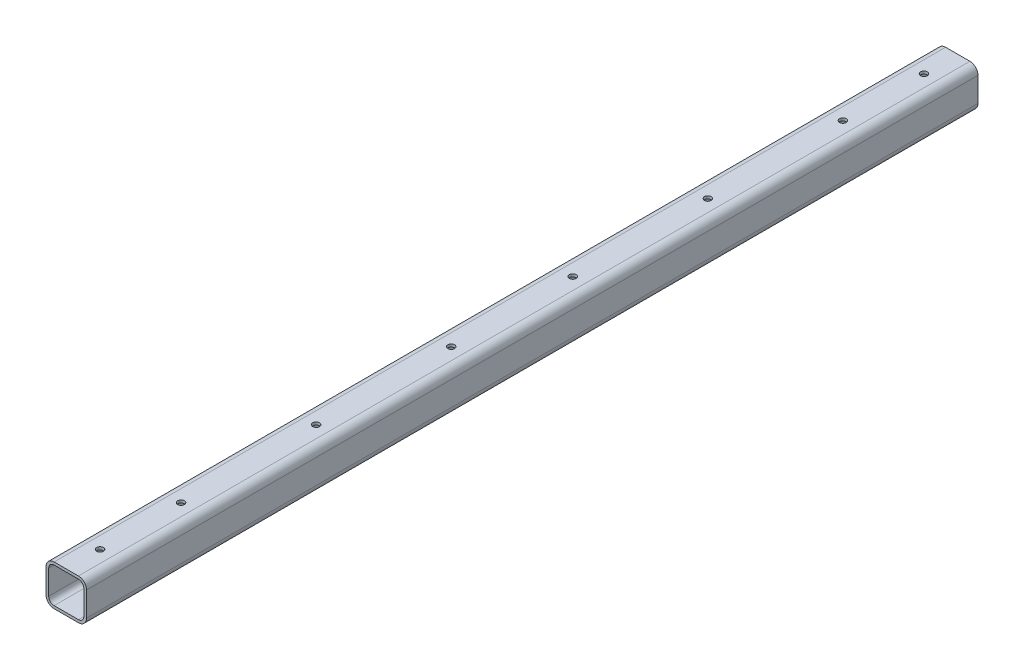
SolidWorks part; units mm, degrees
material "1.0038 (S235JRG2)"
ref_plane "Ebene vorne" through (0, 0, 0) normal (0, 0, 1) x (1, 0, 0)
ref_plane "Ebene oben" through (0, 0, 0) normal (0, 1, 0) x (1, 0, 0)
ref_plane "Ebene rechts" through (0, 0, 0) normal (1, 0, 0) x (0, 0, -1)
sketch "Skizze1" plane through (0, 0, 0) normal (0, 0, 1) x (1, 0, 0)
  line L0 (0, 0) -> (0, 67.8952) construction
  line L1 (-9, 15) -> (9, 15)
  line L2 (0, 0) -> (65.406, 0) construction
  line L3 (15, 9) -> (15, -9)
  line L4 (-15, 9) -> (-15, -9)
  line L5 (-9, -15) -> (9, -15)
  line L6 (-13, 9) -> (-13, -9)
  line L7 (-9, -13) -> (9, -13)
  line L8 (13, 9) -> (13, -9)
  line L9 (-9, 13) -> (9, 13)
  arc A0 (9, 15) -> (15, 9) centre (9, 9) cw
  arc A1 (-9, 15) -> (-15, 9) centre (-9, 9) ccw
  arc A2 (-9, -15) -> (-15, -9) centre (-9, -9) cw
  arc A3 (9, -15) -> (15, -9) centre (9, -9) ccw
  arc A4 (-9, -13) -> (-13, -9) centre (-9, -9) cw
  arc A5 (9, -13) -> (13, -9) centre (9, -9) ccw
  arc A6 (9, 13) -> (13, 9) centre (9, 9) cw
  arc A7 (-9, 13) -> (-13, 9) centre (-9, 9) ccw
  point P12 (15, 0)
  point P13 (0, 15)
  point P19 (-15, 0)
  dimension "D1" = 6
  dimension "D3" = 30
  dimension "D4" = 30
  dimension "D2" = 2
extrude "Aufsatz-Linear austragen1" add sketch "Skizze1" along normal mid plane 660
sketch "Skizze2" plane through (0, -15, 0) normal (0, -1, 0) x (1, 0, 0)
  line L0 (0, 0) -> (0, -370.5853) construction
  line L1 (0, 0) -> (74.1968, 0) construction
  line L2 (-9, -330) -> (9, -330) construction
  circle A0 centre (0, -305) radius 2.5
  circle A1 centre (0, -245) radius 2.5
  circle A2 centre (0, -145) radius 2.5
  circle A3 centre (0, -45) radius 2.5
  circle A4 centre (0, 45) radius 2.5
  circle A5 centre (0, 145) radius 2.5
  circle A6 centre (0, 245) radius 2.5
  circle A7 centre (0, 305) radius 2.5
  dimension "D1" = 25
  dimension "D2" = 60
  dimension "D3" = 100
  dimension "D4" = 100
  dimension "D5" = 45
  dimension "D6" = 5
extrude "Schnitt-Linear austragen1" cut sketch "Skizze2" against normal blind 60
